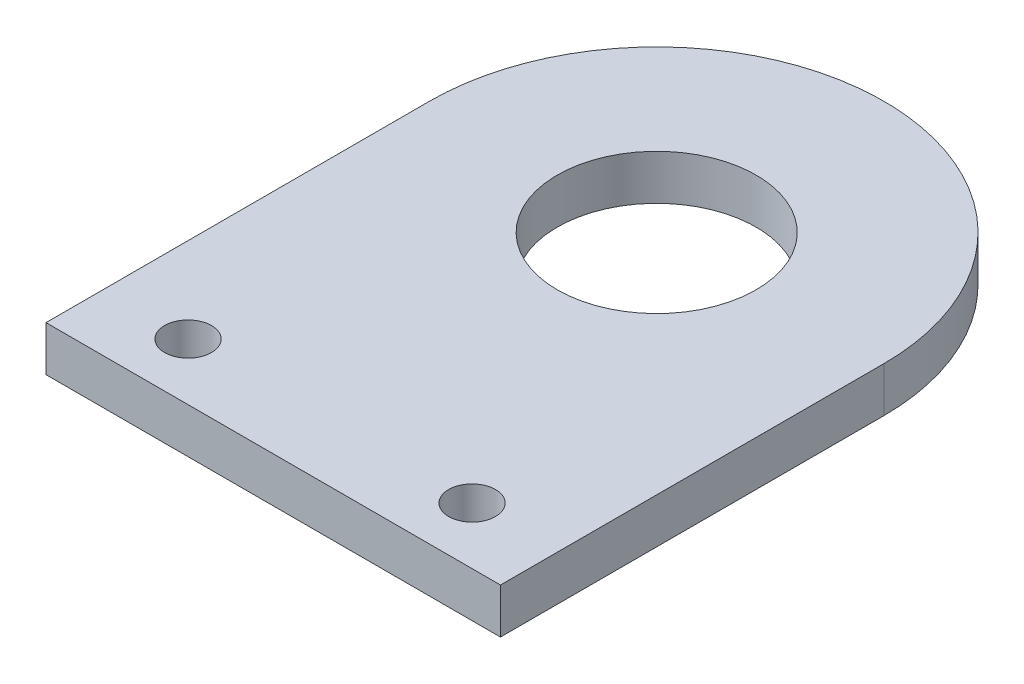
SolidWorks part; units mm, degrees
ref_plane "Front" through (0, 0, 0) normal (0, 0, 1) x (1, 0, 0)
ref_plane "Top" through (0, 0, 0) normal (0, 1, 0) x (1, 0, 0)
ref_plane "Right" through (0, 0, 0) normal (1, 0, 0) x (0, 0, -1)
sketch "Sketch1" plane through (0, 0, 0) normal (0, 1, 0) x (1, 0, 0)
  line L0 (16, 0) -> (16, 27)
  line L1 (0, 0) -> (32, 0)
  line L5 (0, 0) -> (0, 27)
  line L6 (0, 27) -> (16, 27)
  line L7 (32, 0) -> (32, 27)
  line L8 (32, 27) -> (16, 27)
  line L9 (6, 4) -> (26, 4)
  arc A0 (0, 27) -> (32, 27) centre (16, 27) cw
  circle A1 centre (6, 4) radius 1.65
  circle A2 centre (26, 4) radius 1.65
  circle A3 centre (16, 27) radius 7
  point P11 (16, 4)
  dimension "D3" = 20
  dimension "D4" = 4
  dimension "D1" = 27
  dimension "D2" = 32
extrude "Boss-Extrude1" add sketch "Sketch1" along normal blind 3.175
